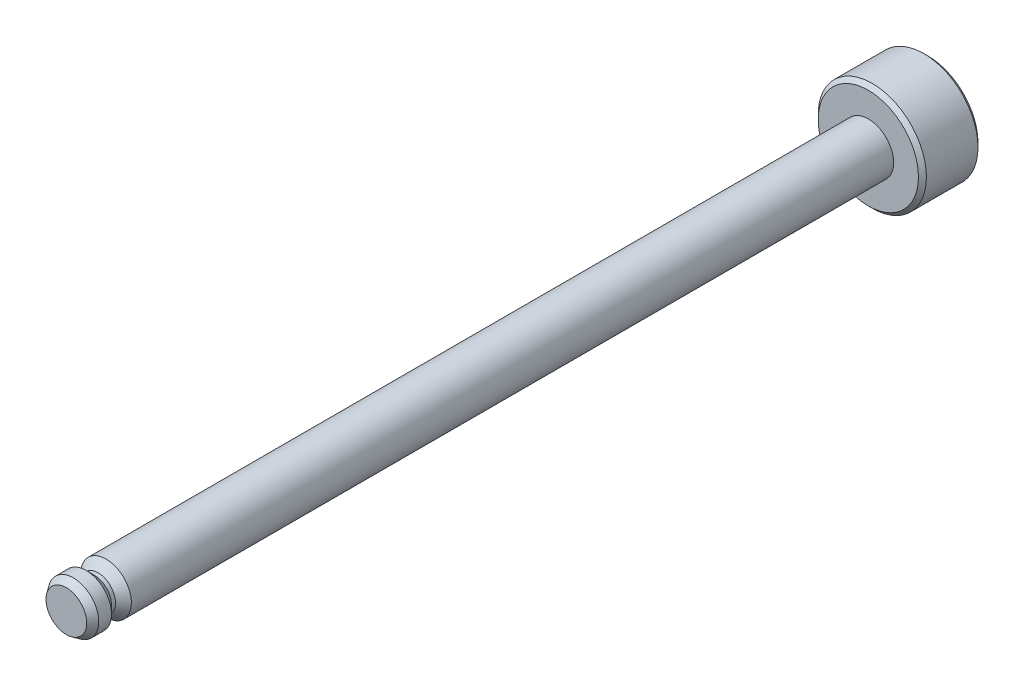
SolidWorks part; units mm, degrees
ref_plane "Front" through (0, 0, 0) normal (0, 0, 1) x (1, 0, 0)
ref_plane "Top" through (0, 0, 0) normal (0, 1, 0) x (1, 0, 0)
ref_plane "Right" through (0, 0, 0) normal (1, 0, 0) x (0, 0, -1)
sketch "Sketch2" plane through (0, 0, 0) normal (0, 0, 1) x (1, 0, 0)
  circle A0 centre (0, 0) radius 1.275
  dimension "D1" = 2.55
extrude "Shaft" add sketch "Sketch2" along normal blind 40.4
sketch "Sketch5" plane through (0, 0, 0) normal (0, 0, 1) x (1, 0, 0)
  circle A0 centre (0, 0) radius 2.725
  dimension "D1" = 5.45
extrude "Head" add sketch "Sketch5" against normal blind 3
chamfer "Chamfer1" distance 0.25 angle 55 1 edges at (1.275, 0, 40.4)
chamfer "Deburs" distance 0.2 angle 45 2 edges at (2.725, 0, 0) (2.725, 0, -3)
sketch "Sketch6" plane through (0, 0, 0) normal (1, 0, 0) x (0, 0, -1)
  line L0 (0, 0) -> (-38.9, 0) construction
  line L1 (-38.9, 0) -> (-38.9, 0.875) construction
  line L2 (0, 1.275) -> (-40.043, 1.275) construction
  line L3 (-39.4, 1.275) -> (-38.4, 1.275)
  line L4 (-38.4, 1.275) -> (-38.8, 0.875)
  line L5 (-38.8, 0.875) -> (-39, 0.875)
  line L6 (-39, 0.875) -> (-39.4, 1.275)
  line L7 (-38.9, 0.875) -> (-38.9, 1.275) construction
  dimension "D1" = 38.9
  dimension "D2" = 0.4
  dimension "D3" = 1
revolve "e-Clip Notch Long" cut sketch "Sketch6" angle 360 about L0
equation "\"D1@Sketch2\"=\"Plastic Hardware OD@Box Assy.Assembly\""
equation "\"D1\"= \"Countersink Diameter@Box Assy.Assembly\" - .3mm"
equation "\"D1@Head\"=\"Countersink Depth@Box Assy.Assembly\""
equation "\"Length\"= 40mm"
equation "\"D1@Shaft\"=\"Length\"+.4mm"
equation "\"D1@Sketch6\"=\"Length\"-1.1mm"
